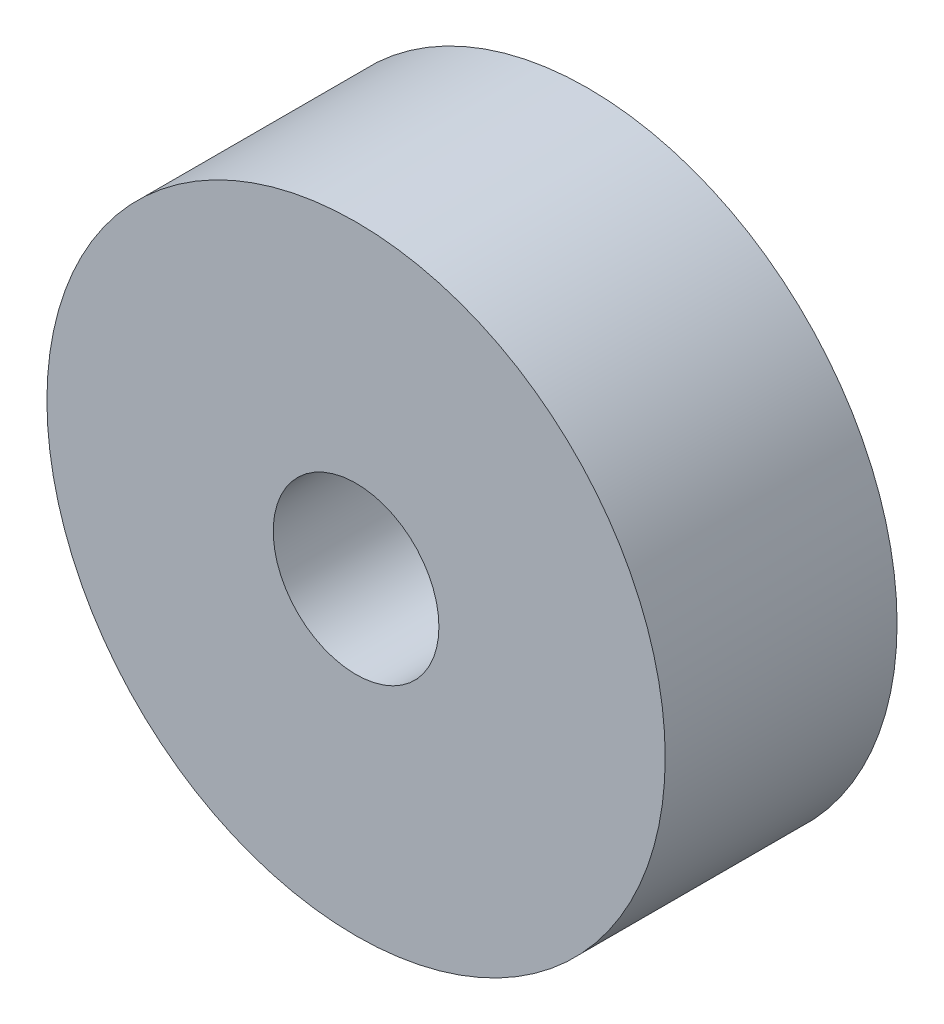
SolidWorks part; units mm, degrees
ref_plane "Front Plane" through (0, 0, 0) normal (0, 0, 1) x (1, 0, 0)
ref_plane "Top Plane" through (0, 0, 0) normal (0, 1, 0) x (1, 0, 0)
ref_plane "Right Plane" through (0, 0, 0) normal (1, 0, 0) x (0, 0, -1)
sketch "Sketch3" plane through (0, 0, 0) normal (0, 0, 1) x (1, 0, 0)
  circle A0 centre (0, 0) radius 40
extrude "Boss-Extrude2" add sketch "Sketch3" along normal blind 30
sketch "Sketch4" plane through (0, 0, 30) normal (0, 0, 1) x (1, 0, 0)
  circle A0 centre (0, 0) radius 10.72
extrude "Cut-Extrude1" cut sketch "Sketch4" against normal blind 30
